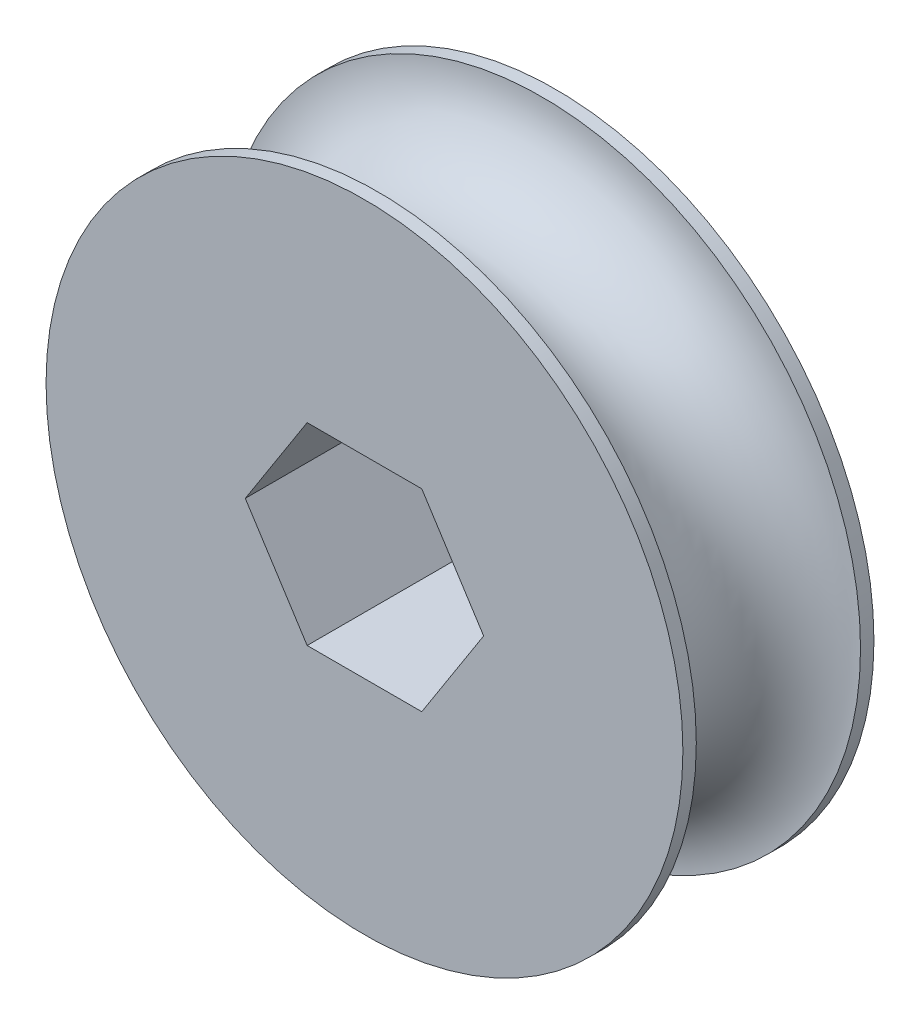
SolidWorks part; units mm, degrees
ref_plane "Plan de face" through (0, 0, 0) normal (0, 0, 1) x (1, 0, 0)
ref_plane "Plan de dessus" through (0, 0, 0) normal (0, 1, 0) x (1, 0, 0)
ref_plane "Plan de droite" through (0, 0, 0) normal (1, 0, 0) x (0, 0, -1)
sketch "Sketch1" plane through (0, 0, 0) normal (0, 0, 1) x (1, 0, 0)
  line L0 (-9, 15.1536) -> (9, 15.1536)
  line L1 (9, 15.1536) -> (18.7143, 0)
  line L2 (18.7143, 0) -> (9, -15.1536)
  line L3 (9, -15.1536) -> (-9, -15.1536)
  line L4 (-9, -15.1536) -> (-18.7143, 0)
  line L5 (-18.7143, 0) -> (-9, 15.1536)
  line L6 (-13.8572, 7.5768) -> (13.8572, -7.5768) construction
  line L7 (-13.8572, -7.5768) -> (13.8572, 7.5768) construction
  circle A0 centre (0, 0) radius 50
  point P11 (0, 0)
  dimension "D1" = 18
  dimension "D2" = 100
extrude "Boss-Extrude1" add sketch "Sketch1" along normal blind 30
sketch "Sketch2" plane through (0, 0, 0) normal (1, 0, 0) x (0, 0, -1)
  line L0 (0, 50) -> (-30, 50) construction
  line L1 (15.9136, 0) -> (-54.0366, 0) construction
  circle A0 centre (-15, 50) radius 12.8935
revolve "Cut-Revolve1" cut sketch "Sketch2" angle 360 about L1
